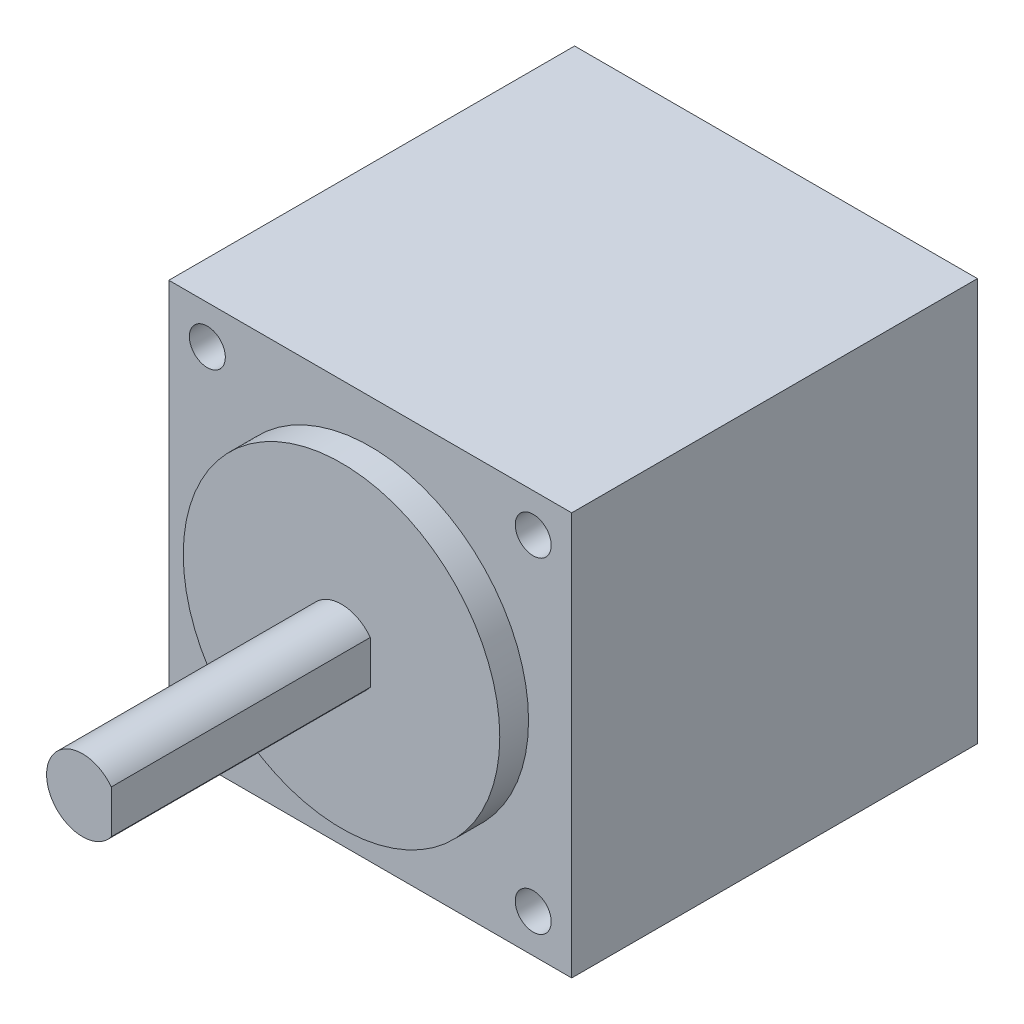
SolidWorks part; units mm, degrees
ref_plane "Front Plane" through (0, 0, 0) normal (0, 0, 1) x (1, 0, 0)
ref_plane "Top Plane" through (0, 0, 0) normal (0, 1, 0) x (1, 0, 0)
ref_plane "Right Plane" through (0, 0, 0) normal (1, 0, 0) x (0, 0, -1)
sketch "Sketch2" plane through (0, 0, 0) normal (0, 0, 1) x (1, 0, 0)
  line L1 (-14, -14) -> (14, -14)
  line L2 (-14, -14) -> (-14, 14)
  line L3 (-14, 14) -> (14, 14)
  line L4 (14, -14) -> (14, 14)
  line L5 (-14, -14) -> (14, 14) construction
  line L6 (-14, 14) -> (14, -14) construction
  point P0 (0, 0)
  dimension "D1" = 28
  dimension "D2" = 28
extrude "Boss-Extrude1" add sketch "Sketch2" against normal blind 28.2
sketch "Sketch3" plane through (0, 0, 0) normal (0, 0, 1) x (1, 0, 0)
  circle A0 centre (0, 0) radius 11
  dimension "D1" = 22
extrude "Boss-Extrude2" add sketch "Sketch3" along normal blind 2
sketch "Sketch4" plane through (0, 0, 0) normal (0, 0, 1) x (1, 0, 0)
  circle A0 centre (0, 0) radius 2.5
extrude "Boss-Extrude3" add sketch "Sketch4" along normal blind 20
sketch "Sketch5" plane through (0, 0, 20) normal (0, 0, 1) x (1, 0, 0)
  line L0 (2, 1.5) -> (2, -1.5)
  circle A0 centre (0, 0) radius 2.5 construction
  circle A1 centre (0, 0) radius 2.5
  point P5 (-2.5, 0)
  circle M2 centre (0, 0) radius 2.5
  dimension "D1" = 4.5
extrude "Cut-Extrude1" cut sketch "Sketch5" against normal up to surface (18 mm away) contours L0 M2
sketch "Sketch6" plane through (0, 0, 0) normal (0, 0, 1) x (1, 0, 0)
  line L1 (-11.325, -11.325) -> (11.325, -11.325)
  line L2 (-11.325, -11.325) -> (-11.325, 11.325)
  line L3 (-11.325, 11.325) -> (11.325, 11.325)
  line L4 (11.325, -11.325) -> (11.325, 11.325)
  line L5 (-11.325, -11.325) -> (11.325, 11.325) construction
  line L6 (-11.325, 11.325) -> (11.325, -11.325) construction
  point P0 (0, 0)
  point P7 (-11.325, 11.325)
  point P8 (11.325, 11.325)
  point P9 (11.325, -11.325)
  point P10 (-11.325, -11.325)
  dimension "D1" = 22.65
hole_wizard "Ø2.5mm Dowel Hole1" positions "Sketch7" profile "Sketch9" hole size "Ø2.5" standard "ANSI Metric"
sketch "Sketch7" plane through (0, 0, 0) normal (0, 0, 1) x (1, 0, 0)
  point P0 (-11.325, 11.325)
  point P3 (11.325, 11.325)
  point P6 (11.325, -11.325)
  point P9 (-11.325, -11.325)
sketch "Sketch9" plane through (-11.325, 11.325, 0) normal (1, 0, 0) x (0, -1, 0)
  line L0 (0, 0) -> (0, 4.7511)
  line L1 (0, 4.7511) -> (1.25, 4)
  line L2 (1.25, 4) -> (1.25, 0)
  line L5 (1.25, 0) -> (0, 0)
  line L10 (0, 4.7511) -> (-1.25, 4) construction
  line L11 (0, -6.35) -> (0, 107.95) construction
  dimension "Hole Dia." = 2.5
  dimension "Hole Depth" = 4
  dimension "Drill Angle" = 118
